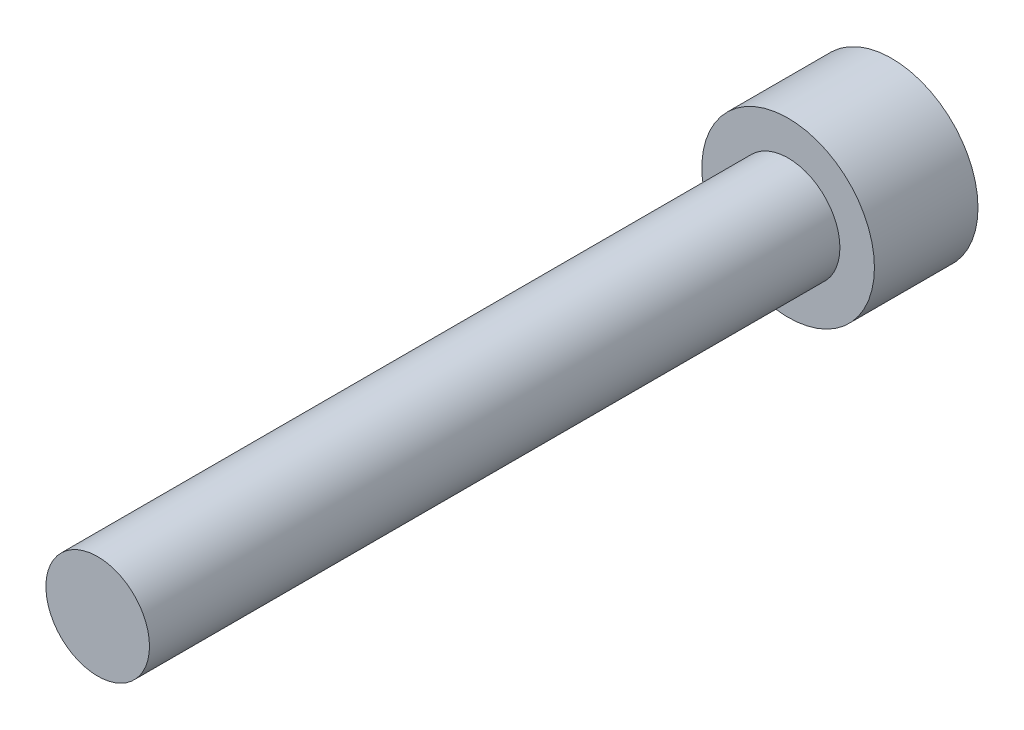
SolidWorks part; units mm, degrees
ref_plane "正面" through (0, 0, 0) normal (0, 0, 1) x (1, 0, 0)
ref_plane "平面" through (0, 0, 0) normal (0, 1, 0) x (1, 0, 0)
ref_plane "右側面" through (0, 0, 0) normal (1, 0, 0) x (0, 0, -1)
sketch "ｽｹｯﾁ1" plane through (0, 0, 0) normal (0, 0, 1) x (1, 0, 0)
  circle A0 centre (0, 0) radius 5
  dimension "D1" = 10
extrude "ﾎﾞｽ - 押し出し1" add sketch "ｽｹｯﾁ1" along normal blind 6
sketch "ｽｹｯﾁ2" plane through (0, 0, 6) normal (0, 0, 1) x (1, 0, 0)
  circle A0 centre (0, 0) radius 3
  dimension "D1" = 6
extrude "ﾎﾞｽ - 押し出し2" add sketch "ｽｹｯﾁ2" along normal blind 40
cosmetic thread "ねじ山1" parameters "D2"=5
sketch "ｽｹｯﾁ3" plane through (0, 0, 0) normal (0, 0, -1) x (-1, 0, 0)
  line L1 (2.4446, 2.3616) -> (-0.8229, 3.2979)
  line L2 (-0.8229, 3.2979) -> (-3.2675, 0.9363)
  line L3 (-3.2675, 0.9363) -> (-2.4446, -2.3616)
  line L4 (-2.4446, -2.3616) -> (0.8229, -3.2979)
  line L5 (0.8229, -3.2979) -> (3.2675, -0.9363)
  line L6 (3.2675, -0.9363) -> (2.4446, 2.3616)
  circle A0 centre (0, 0) radius 2.9436 construction
extrude "ｶｯﾄ - 押し出し1" cut sketch "ｽｹｯﾁ3" against normal blind 3
